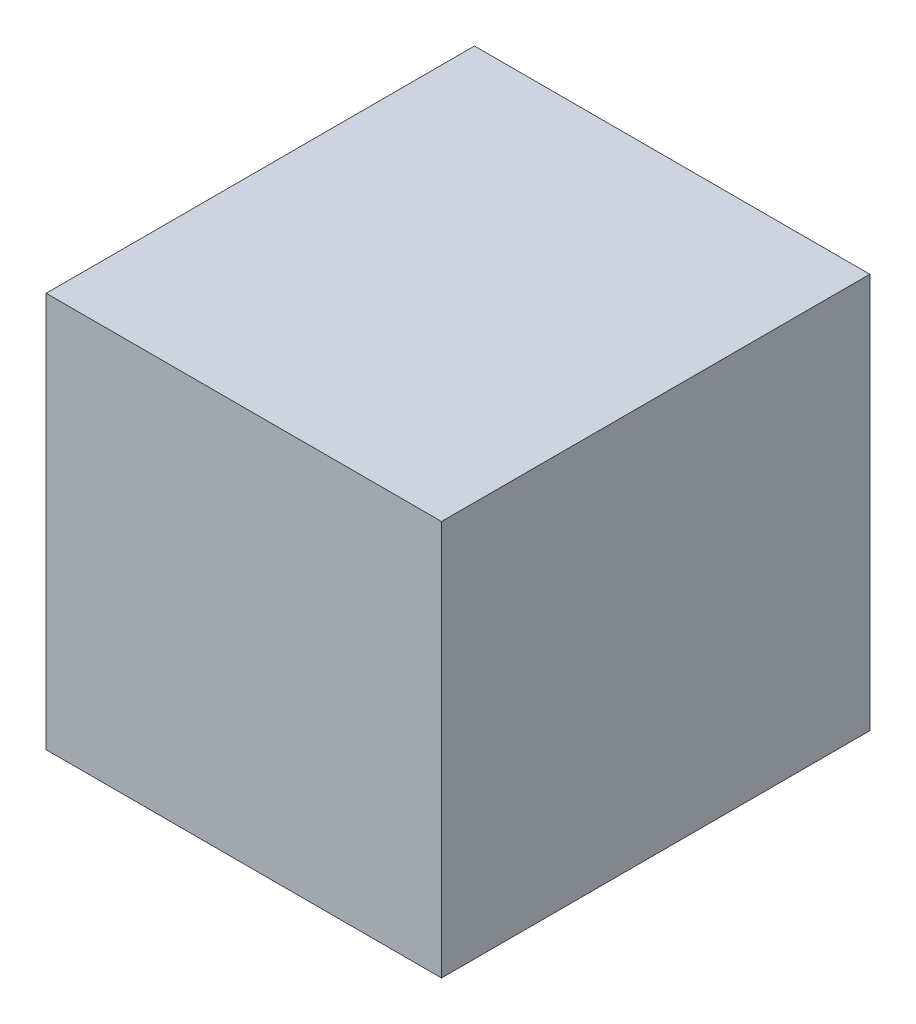
SolidWorks part; units mm, degrees
ref_plane "Front Plane" through (0, 0, 0) normal (0, 0, 1) x (1, 0, 0)
ref_plane "Top Plane" through (0, 0, 0) normal (0, 1, 0) x (1, 0, 0)
ref_plane "Right Plane" through (0, 0, 0) normal (1, 0, 0) x (0, 0, -1)
sketch "Sketch1" plane through (0, 0, 0) normal (0, 1, 0) x (1, 0, 0)
  line L1 (-60, -65) -> (60, -65)
  line L2 (-60, -65) -> (-60, 65)
  line L3 (-60, 65) -> (60, 65)
  line L4 (60, -65) -> (60, 65)
  line L5 (-60, -65) -> (60, 65) construction
  line L6 (-60, 65) -> (60, -65) construction
  point P0 (0, 0)
  dimension "D1" = 120
  dimension "D2" = 130
extrude "Boss-Extrude1" add sketch "Sketch1" along normal mid plane 120
